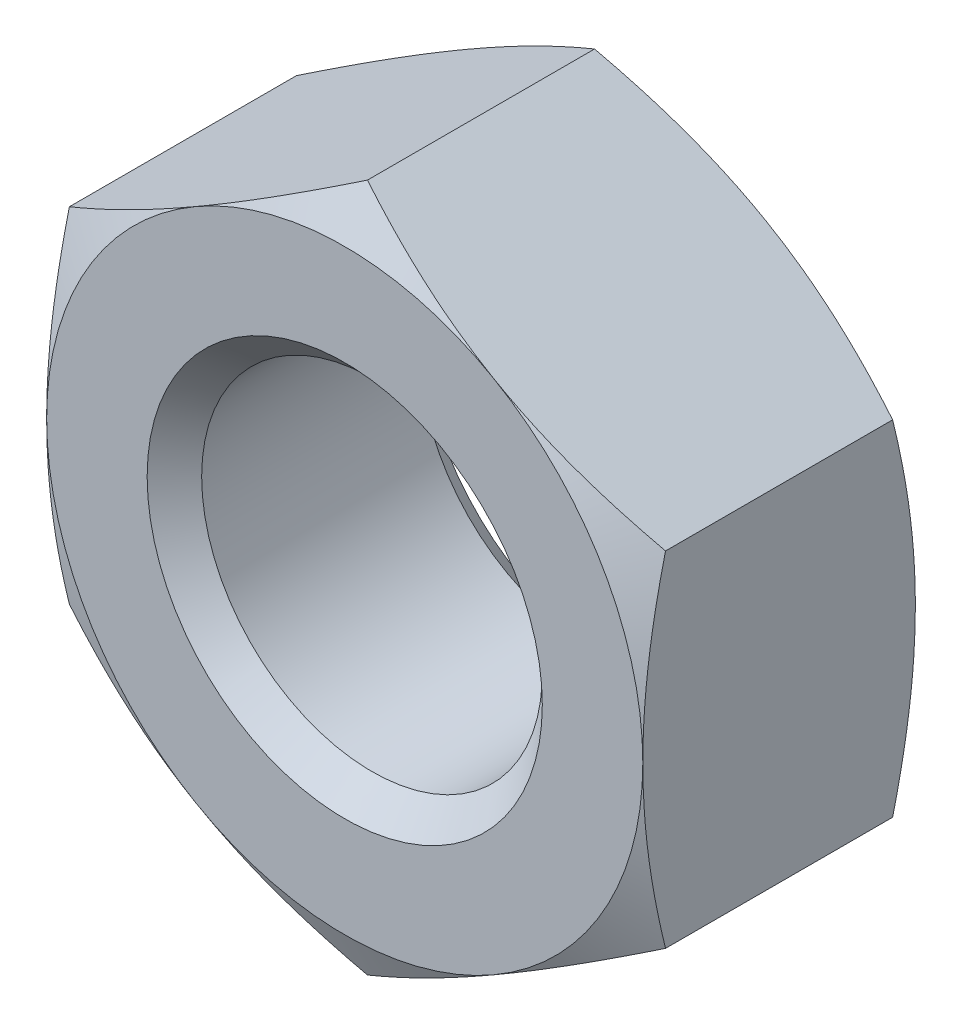
SolidWorks part; units mm, degrees
material "Plain Carbon Steel"
ref_plane "Front Plane" through (0, 0, 0) normal (0, 0, 1) x (1, 0, 0)
ref_plane "Top Plane" through (0, 0, 0) normal (0, 1, 0) x (1, 0, 0)
ref_plane "Right Plane" through (0, 0, 0) normal (1, 0, 0) x (0, 0, -1)
sketch "Sketch1" plane through (0, 0, 0) normal (0, 0, 1) x (1, 0, 0)
  line L1 (0, -4.0415) -> (3.5, -2.0207)
  line L2 (3.5, -2.0207) -> (3.5, 2.0207)
  line L3 (3.5, 2.0207) -> (0, 4.0415)
  line L4 (0, 4.0415) -> (-3.5, 2.0207)
  line L5 (-3.5, 2.0207) -> (-3.5, -2.0207)
  line L6 (-3.5, -2.0207) -> (0, -4.0415)
  circle A0 centre (0, 0) radius 3.5 construction
  circle A1 centre (0, 0) radius 2
  dimension "D2" = 4
  dimension "D1" = 7
extrude "Boss-Extrude1" add sketch "Sketch1" along normal blind 3.2
sketch "Sketch2" plane through (0, 0, 0) normal (1, 0, 0) x (0, 0, -1)
  line L0 (-3.2, 4.0415) -> (-3.2, 3.5)
  line L1 (-3.2, 2.0207) -> (-3.2, 4.0415) construction
  line L2 (-3.2, 3.5) -> (-2.9333, 4.0415)
  line L3 (-3.2, 4.0415) -> (0, 4.0415) construction
  line L4 (-2.9333, 4.0415) -> (-3.2, 4.0415)
  line L5 (-0.2667, 4.0415) -> (0, 4.0415)
  line L6 (0, 4.0415) -> (0, 3.5)
  line L7 (0, 2.0207) -> (0, 4.0415) construction
  line L8 (0, 3.5) -> (-0.2667, 4.0415)
  line L9 (-2.9333, 4.0415) -> (-2.6667, 4.0415) construction
  line L10 (-2.6667, 4.0415) -> (-2.4, 4.0415) construction
  line L11 (-2.4, 4.0415) -> (-2.1333, 4.0415) construction
  line L12 (-2.1333, 4.0415) -> (-1.8667, 4.0415) construction
  line L13 (-1.8667, 4.0415) -> (-1.6, 4.0415) construction
  line L14 (-1.6, 4.0415) -> (-1.3333, 4.0415) construction
  line L15 (-1.3333, 4.0415) -> (-1.0667, 4.0415) construction
  line L16 (-1.0667, 4.0415) -> (-0.8, 4.0415) construction
  line L17 (-0.8, 4.0415) -> (-0.5333, 4.0415) construction
  line L18 (0, 0) -> (-3.2, 0) construction
  line L19 (-3.2, -2.0207) -> (-3.2, 2.0207) construction
  line L20 (-3.2, 2) -> (-2.88, 2)
  line L21 (-2.88, 2) -> (-3.2, 2.32)
  line L22 (-3.2, 2.32) -> (-3.2, 2)
  line L23 (0, 2) -> (-0.32, 2)
  line L24 (0, -2.0207) -> (0, 2.0207) construction
  line L25 (-0.32, 2) -> (0, 2.32)
  line L26 (0, 2.32) -> (0, 2)
  line L29 (-2.88, 2) -> (-2.56, 2) construction
  line L30 (-2.56, 2) -> (-2.24, 2) construction
  line L31 (-2.24, 2) -> (-1.92, 2) construction
  line L32 (-1.92, 2) -> (-1.6, 2) construction
  line L33 (-1.6, 2) -> (-1.28, 2) construction
  line L34 (-1.28, 2) -> (-0.96, 2) construction
  line L35 (-0.96, 2) -> (-0.64, 2) construction
  line L36 (-0.64, 2) -> (-0.32, 2) construction
  line L37 (-0.5333, 4.0415) -> (-0.2667, 4.0415) construction
  dimension "D1" = 7
revolve "Cut-Revolve1" cut sketch "Sketch2" angle 360 about L18
